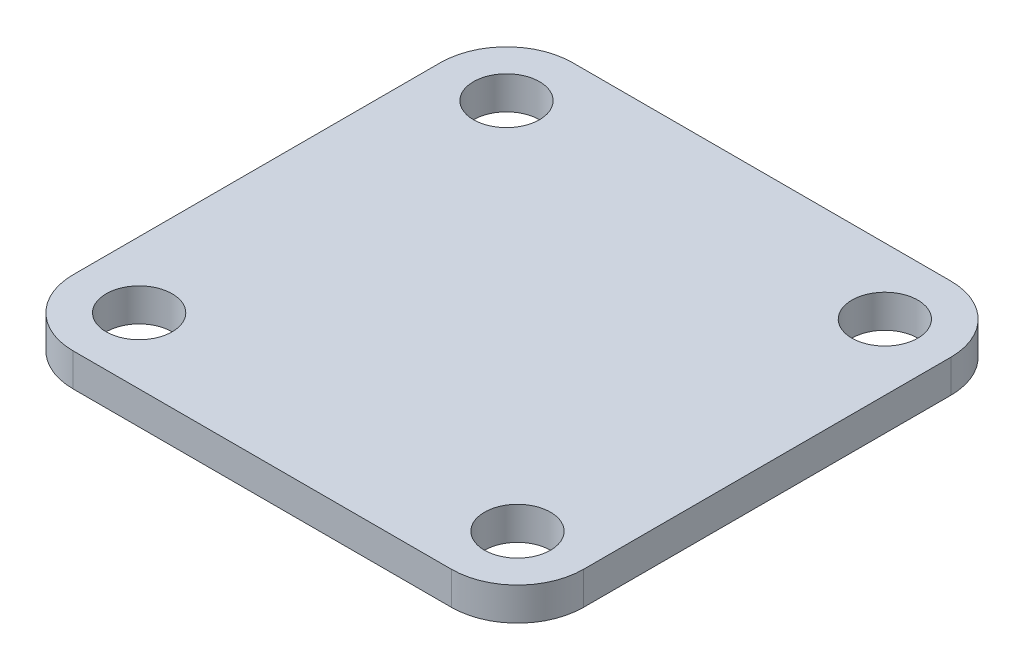
SolidWorks part; units mm, degrees
ref_plane "Front Plane" through (0, 0, 0) normal (0, 0, 1) x (1, 0, 0)
ref_plane "Top Plane" through (0, 0, 0) normal (0, 1, 0) x (1, 0, 0)
ref_plane "Right Plane" through (0, 0, 0) normal (1, 0, 0) x (0, 0, -1)
sketch "Sketch1" plane through (0, 0, 0) normal (0, 1, 0) x (1, 0, 0)
  line L1 (-11.6, 11.35) -> (11.6, 11.35)
  line L2 (-11.6, 11.35) -> (-11.6, -11.35)
  line L3 (-11.6, -11.35) -> (11.6, -11.35)
  line L4 (11.6, 11.35) -> (11.6, -11.35)
  line L5 (-11.6, 11.35) -> (11.6, -11.35) construction
  line L6 (-11.6, -11.35) -> (11.6, 11.35) construction
  point P0 (0, 0)
  dimension "D1" = 23.2
  dimension "D2" = 22.7
extrude "Boss-Extrude1" add sketch "Sketch1" along normal blind 1.5
fillet "Fillet1" radius 3 4 edges at (-11.6, 0.75, -11.35) (11.6, 0.75, -11.35) (-11.6, 0.75, 11.35) (11.6, 0.75, 11.35)
sketch "Sketch2" plane through (0, 1.5, 0) normal (0, 1, 0) x (1, 0, 0)
  circle A0 centre (-8.6, 8.35) radius 1.5
  circle A1 centre (8.6, 8.35) radius 1.5
  circle A2 centre (8.6, -8.35) radius 1.5
  circle A3 centre (-8.6, -8.35) radius 1.5
  dimension "D1" = 3
extrude "Cut-Extrude1" cut sketch "Sketch2" against normal through all
